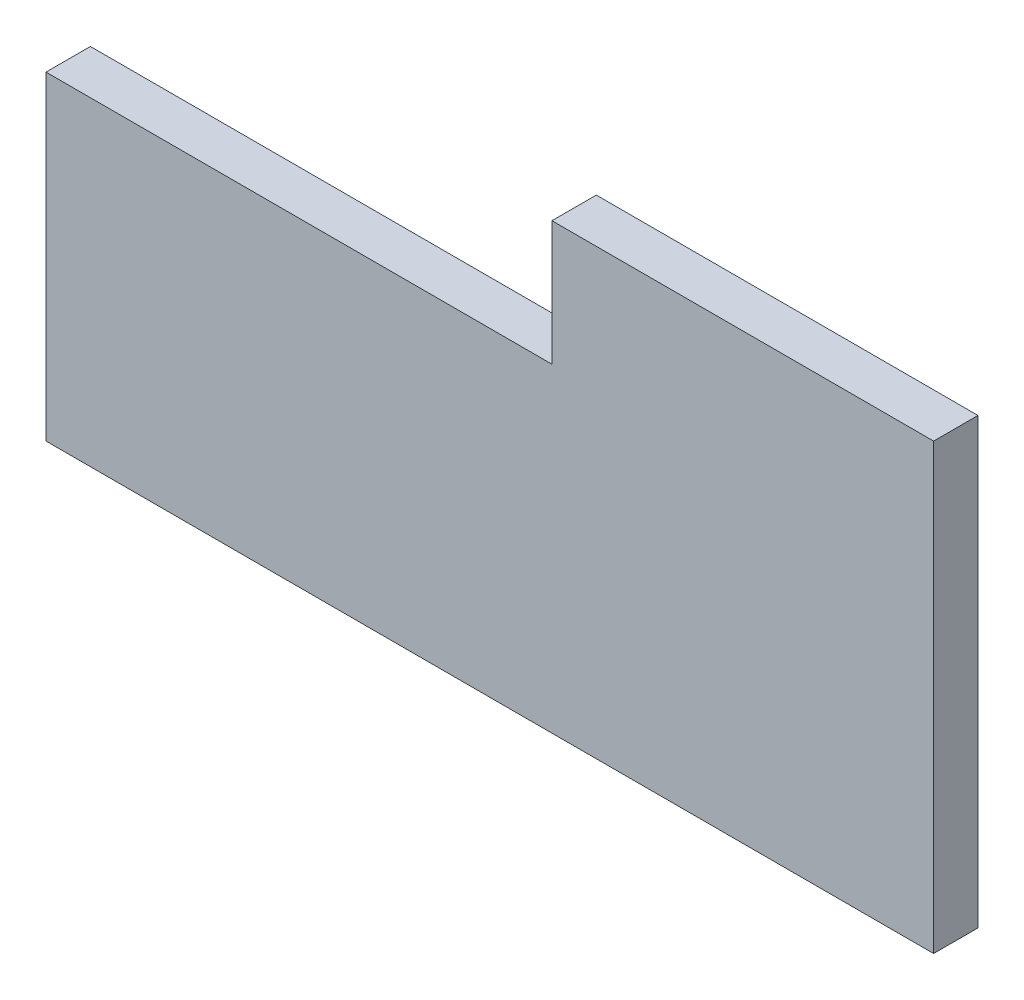
SolidWorks part; units mm, degrees
ref_plane "Front" through (0, 0, 0) normal (0, 0, 1) x (1, 0, 0)
ref_plane "Top" through (0, 0, 0) normal (0, 1, 0) x (1, 0, 0)
ref_plane "Right" through (0, 0, 0) normal (1, 0, 0) x (0, 0, -1)
sketch "Sketch1" plane through (0, 0, 0) normal (0, 0, 1) x (1, 0, 0)
  line L0 (-127, 27.94) -> (17.78, 27.94)
  line L1 (17.78, 27.94) -> (17.78, 63.5)
  line L2 (17.78, 63.5) -> (127, 63.5)
  line L3 (127, 63.5) -> (127, -63.5)
  line L4 (127, -63.5) -> (-127, -63.5)
  line L5 (-127, -63.5) -> (-127, 27.94)
  line L6 (50, 0) -> (-50, 0) construction
  line L7 (0, -50) -> (0, 50) construction
  point P6 (127, 0)
  point P9 (0, -63.5)
  dimension "D1" = 91.44
  dimension "D2" = 35.56
  dimension "D3" = 109.22
  dimension "D4" = 144.78
extrude "Boss-Extrude1" add sketch "Sketch1" along normal mid plane 12.7 contours L3 L4 L5 L0 L1 L2
